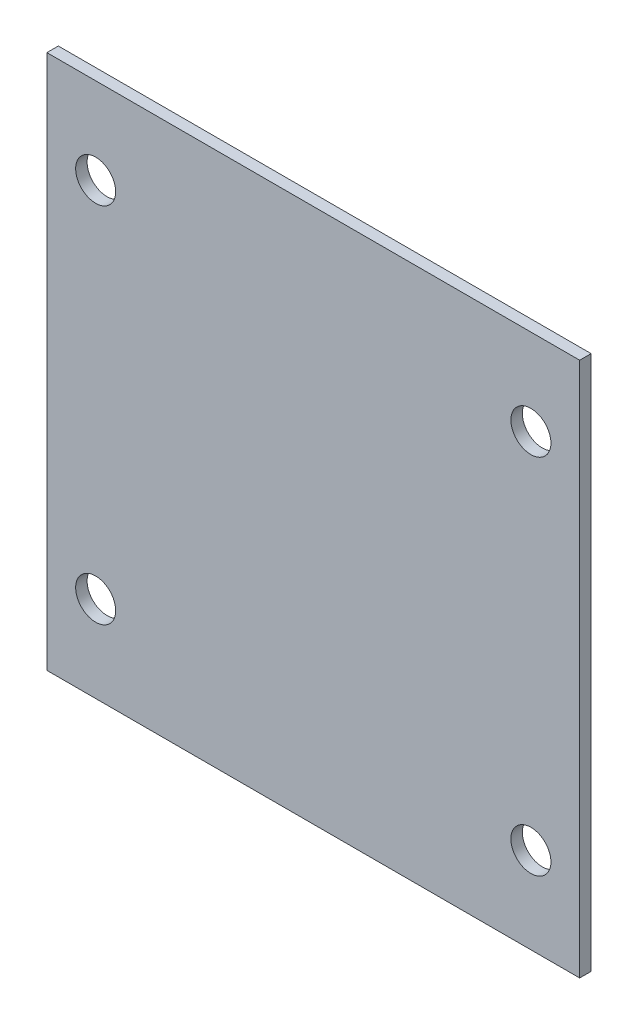
SolidWorks part; units mm, degrees
ref_plane "Front Plane" through (0, 0, 0) normal (0, 0, 1) x (1, 0, 0)
ref_plane "Top Plane" through (0, 0, 0) normal (0, 1, 0) x (1, 0, 0)
ref_plane "Right Plane" through (0, 0, 0) normal (1, 0, 0) x (0, 0, -1)
sketch "Sketch1" plane through (0, 0, 0) normal (0, 0, 1) x (1, 0, 0)
  line L0 (-19.0315, 15.8627) -> (-19.0315, -15.8627) construction
  line L1 (-23.2974, 23.3945) -> (23.2974, 23.3945)
  line L2 (-23.2974, 23.3945) -> (-23.2974, -23.3945)
  line L3 (-23.2974, -23.3945) -> (23.2974, -23.3945)
  line L4 (23.2974, 23.3945) -> (23.2974, -23.3945)
  line L5 (-23.2974, 23.3945) -> (23.2974, -23.3945) construction
  line L6 (-23.2974, -23.3945) -> (23.2974, 23.3945) construction
  line L7 (-19.0315, -15.8627) -> (19.0315, -15.8627) construction
  line L8 (19.0315, -15.8627) -> (19.0315, 15.8627) construction
  line L9 (19.0315, 15.8627) -> (-19.0315, 15.8627) construction
  line L10 (0, 15.8627) -> (0, -15.8627) construction
  circle A0 centre (-19.0315, 15.8627) radius 1.75
  circle A1 centre (19.0315, 15.8627) radius 1.75
  circle A2 centre (19.0315, -15.8627) radius 1.75
  circle A3 centre (-19.0315, -15.8627) radius 1.75
  point P0 (0, 0)
  point P13 (0, 0)
  point P17 (0, 0)
  dimension "D1" = 3.5
  dimension "D2" = 46.5948
  dimension "D3" = 46.789
  dimension "D4" = 31.7254
  dimension "D5" = 38.063
extrude "Boss-Extrude1" add sketch "Sketch1" along normal blind 1
